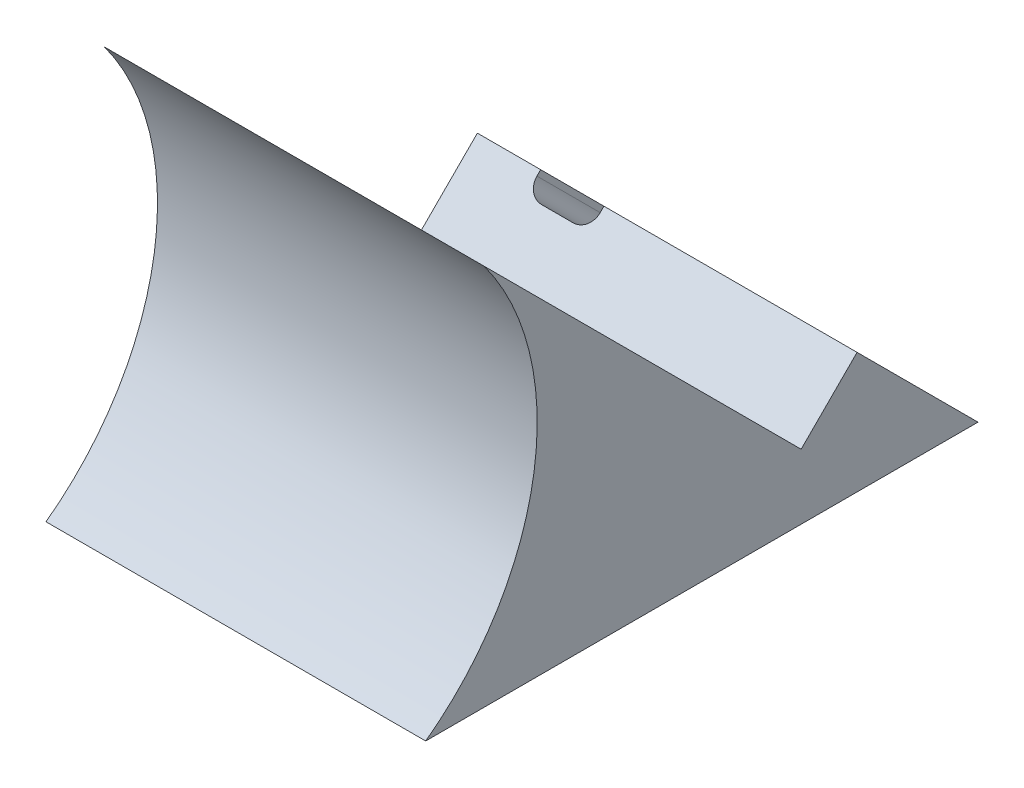
SolidWorks part; units mm, degrees
ref_plane "Front Plane" through (0, 0, 0) normal (0, 0, 1) x (1, 0, 0)
ref_plane "Top Plane" through (0, 0, 0) normal (0, 1, 0) x (1, 0, 0)
ref_plane "Right Plane" through (0, 0, 0) normal (1, 0, 0) x (0, 0, -1)
sketch "Sketch2" plane through (0, 0, 0) normal (1, 0, 0) x (0, 0, -1)
  line L0 (0, 30) -> (-42.4264, 72.4264)
  line L1 (0, 0) -> (-53.5131, 0)
  line L6 (55, 0) -> (-55, 0) construction
  line L7 (30, 0) -> (0, 0)
  line L8 (0, 30) -> (10.6066, 40.6066)
  line L11 (10.6066, 40.6066) -> (51.2132, 0)
  line L12 (51.2132, 0) -> (0, 0)
  arc A0 (-42.4264, 72.4264) -> (-53.5131, 0) centre (-84.183, 41.7566) cw
  dimension "D1" = 30
  dimension "D2" = 60
  dimension "D3" = 15
extrude "Boss-Extrude2" add sketch "Sketch2" along normal blind 72 contours L0 A0 L1 L7 L12 L11 L8
sketch "Sketch3" plane through (0, 25.6066, -25.6066) normal (0, 0.7071, -0.7071) x (1, 0, 0)
  line L0 (72, -21.2132) -> (0, -21.2132) construction
  line L1 (12, -21.2132) -> (24, -21.2132)
  line L2 (12, -21.2132) -> (12, 18.7868)
  line L3 (12, 18.7868) -> (24, 18.7868)
  line L4 (24, -21.2132) -> (24, 18.7868)
  line L5 (0, -21.2132) -> (0, 36.2132) construction
  dimension "D1" = 12
  dimension "D2" = 12
  dimension "D3" = 40
extrude "Cut-Extrude1" cut sketch "Sketch3" against normal blind 4
sketch "Sketch4" plane through (72, 0, 0) normal (1, 0, 0) x (0, 0, -1)
  line L0 (0, 30) -> (17.6777, 12.3223)
  line L1 (17.6777, 12.3223) -> (28.2843, 22.9289)
  line L2 (10.6066, 40.6066) -> (51.2132, 0) construction
  line L3 (28.2843, 22.9289) -> (10.6066, 40.6066)
  line L4 (10.6066, 40.6066) -> (0, 30)
  dimension "D1" = 25
extrude "Cut-Extrude2" cut sketch "Sketch4" against normal through all
sketch "Sketch5" plane through (0, 25.6066, -25.6066) normal (0, 0.7071, -0.7071) x (1, 0, 0)
  line L1 (24, 18.7868) -> (12, 18.7868)
  line L2 (24, 18.7868) -> (24, 32.2311)
  line L3 (24, 32.2311) -> (12, 32.2311)
  line L4 (12, 18.7868) -> (12, 32.2311)
extrude "Cut-Extrude3" cut sketch "Sketch5" against normal up to surface (4 mm away)
chamfer "Chamfer1" distance 3.2 angle 45 1 edges at (18, 2.8158, -48.3974)
fillet "Fillet1" radius 3 2 edges at (24, 10.0503, -35.5061) (12, 10.0503, -35.5061)
